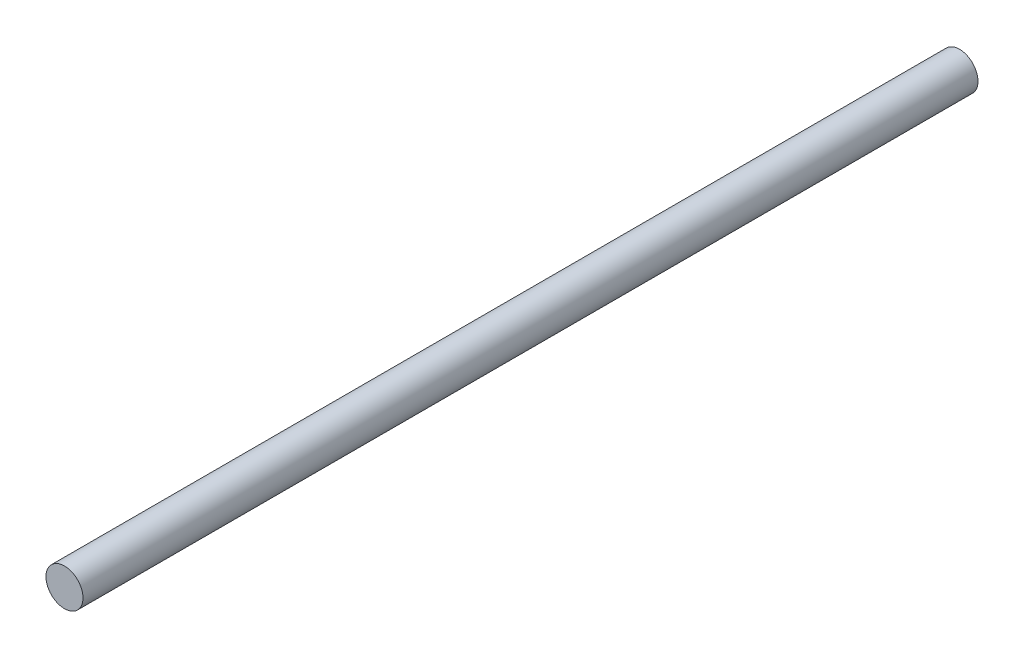
SolidWorks part; units mm, degrees
ref_plane "前视基准面" through (0, 0, 0) normal (0, 0, 1) x (1, 0, 0)
ref_plane "上视基准面" through (0, 0, 0) normal (0, 1, 0) x (1, 0, 0)
ref_plane "右视基准面" through (0, 0, 0) normal (1, 0, 0) x (0, 0, -1)
other "Configuration Table"
sketch "草图1" plane through (0, 0, 0) normal (0, 0, 1) x (1, 0, 0)
  circle A0 centre (0, 0) radius 6
  dimension "diameter" = 12
extrude "Cable" add sketch "草图1" along normal blind 290
